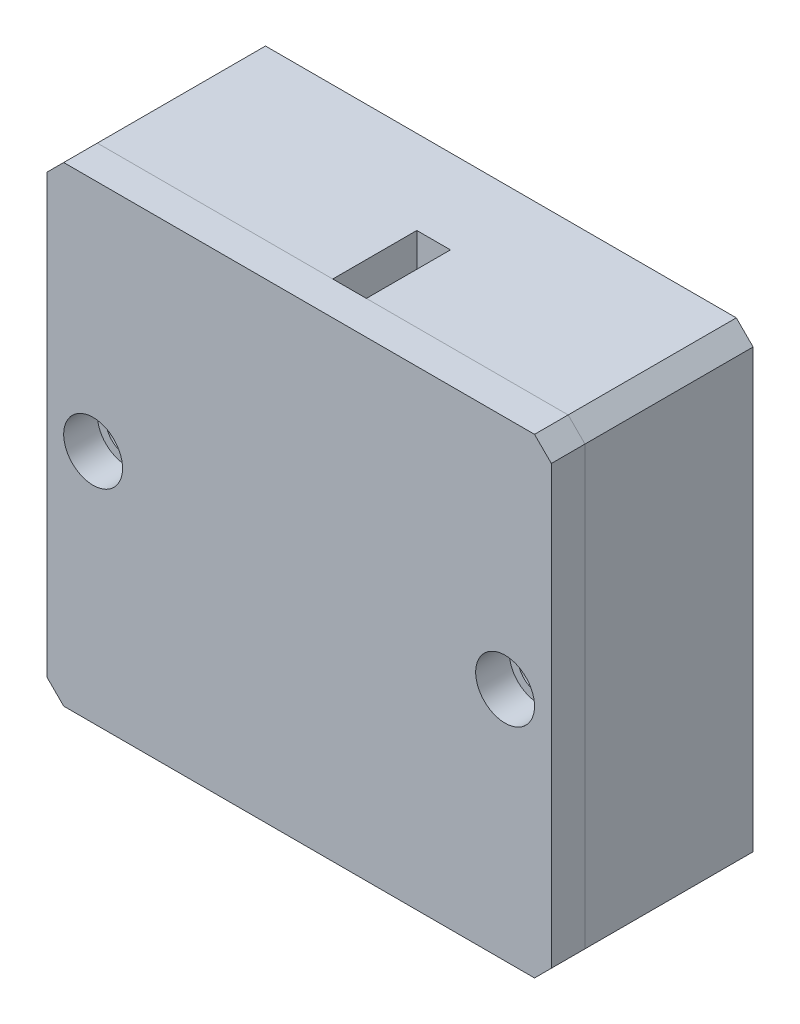
SolidWorks part; units mm, degrees
ref_plane "Front" through (0, 0, 0) normal (0, 0, 1) x (1, 0, 0)
ref_plane "Top" through (0, 0, 0) normal (0, 1, 0) x (1, 0, 0)
ref_plane "Right" through (0, 0, 0) normal (1, 0, 0) x (0, 0, -1)
sketch "Sketch1" plane through (0, 0, 0) normal (0, 0, 1) x (1, 0, 0)
  line L1 (-15, 14) -> (15, 14)
  line L2 (-15, 14) -> (-15, -14)
  line L3 (-15, -14) -> (15, -14)
  line L4 (15, 14) -> (15, -14)
  line L5 (-15, 14) -> (15, -14) construction
  line L6 (-15, -14) -> (15, 14) construction
  point P0 (0, 0)
  dimension "D1" = 30
  dimension "D2" = 28
extrude "Boss-Extrude1" add sketch "Sketch1" along normal blind 10
sketch "Sketch2" plane through (0, 0, 10) normal (0, 0, 1) x (1, 0, 0)
  line L0 (0, 14) -> (0, 12)
  line L1 (15, 14) -> (-15, 14) construction
  line L2 (0, 12) -> (-9.5, 12)
  line L3 (-9.5, 12) -> (-9.5, -14)
  line L4 (-15, -14) -> (15, -14) construction
  line L12 (0, 0) -> (0, 14) construction
  line L13 (9.5, 12) -> (9.5, -14)
  line L14 (2, 12) -> (9.5, 12)
  line L15 (2, 14) -> (2, 12)
  line L16 (0, 14) -> (2, 14)
  line L17 (-9.5, -14) -> (9.5, -14)
  point P17 (-1.527, 12.8159)
  point P18 (0, 0)
  point P19 (0, 0)
  point P20 (2.2542, 13)
  point P21 (2.2542, 15)
  point P22 (1, 14)
  point P23 (2, 10.5)
  dimension "D1" = 19
  dimension "D2" = 2
  dimension "D3" = 2
  dimension "D4" = 1
extrude "Cut-Extrude1" cut sketch "Sketch2" against normal offset from surface (5 mm away) 5 up to face at (0, 0, 0)
sketch "Sketch3" plane through (0, 0, 5) normal (0, 0, 1) x (1, 0, 0)
  line L0 (9.5, -14) -> (9.5, 12) construction
  line L1 (-9.5, -14) -> (9.5, -14)
  line L2 (-9.5, -14) -> (-9.5, -5)
  line L3 (-9.5, -5) -> (9.5, -5)
  line L4 (9.5, -14) -> (9.5, -5)
  line L5 (-9.5, 12) -> (0, 12) construction
  line L6 (0, 14) -> (2, 14) construction
  circle A0 centre (1, 10.882) radius 1.5
  point P13 (1, 14)
  point P16 (1, 8.8166)
  dimension "D2" = 3
  dimension "D1" = 17
extrude "Cut-Extrude2" cut sketch "Sketch3" against normal blind 3
chamfer "Chamfer1" distance 1 angle 45 4 edges at (15, 14, 5) (-15, 14, 5) (-15, -14, 5) (15, -14, 5)
sketch "Sketch4" plane through (0, 0, 10) normal (0, 0, 1) x (1, 0, 0)
  line L0 (0, -14) -> (0, 0) construction
  line L1 (-9.5, -14) -> (9.5, -14) construction
  circle A0 centre (-12.25, 0) radius 1.25
  circle A1 centre (12.25, 0) radius 1.25
  dimension "D1" = 2.5
  dimension "D2" = 24.5
extrude "Cut-Extrude3" cut sketch "Sketch4" against normal blind 8
sketch "Sketch5" plane through (0, 0, 10) normal (0, 0, 1) x (1, 0, 0)
  line L0 (-14, 14) -> (-15, 13)
  line L1 (-15, 13) -> (-15, -13)
  line L2 (-15, -13) -> (-14, -14)
  line L3 (-14, -14) -> (14, -14)
  line L4 (14, -14) -> (15, -13)
  line L5 (15, -13) -> (15, 13)
  line L6 (15, 13) -> (14, 14)
  line L7 (14, 14) -> (-14, 14)
extrude "Boss-Extrude2" add sketch "Sketch5" along normal blind 2 separate body
sketch "Sketch6" plane through (0, 0, 12) normal (0, 0, 1) x (1, 0, 0)
  circle A0 centre (-12.25, 0) radius 1.75
  circle A1 centre (12.25, 0) radius 1.75
  dimension "D1" = 3.5
extrude "Cut-Extrude4" cut sketch "Sketch6" against normal up to next (2 mm away)
sketch "Sketch7" plane through (0, 0, 10) normal (0, 0, -1) x (-1, 0, 0)
  line L0 (14, -14) -> (-14, -14) construction
  line L1 (-9, -14) -> (9, -14)
  line L2 (-9, -14) -> (-9, 9)
  line L3 (-9, 9) -> (9, 9)
  line L4 (9, -14) -> (9, 9)
  point P6 (0, 9)
  dimension "D1" = 23
  dimension "D2" = 0.5
extrude "Boss-Extrude3" add sketch "Sketch7" along normal blind 2
